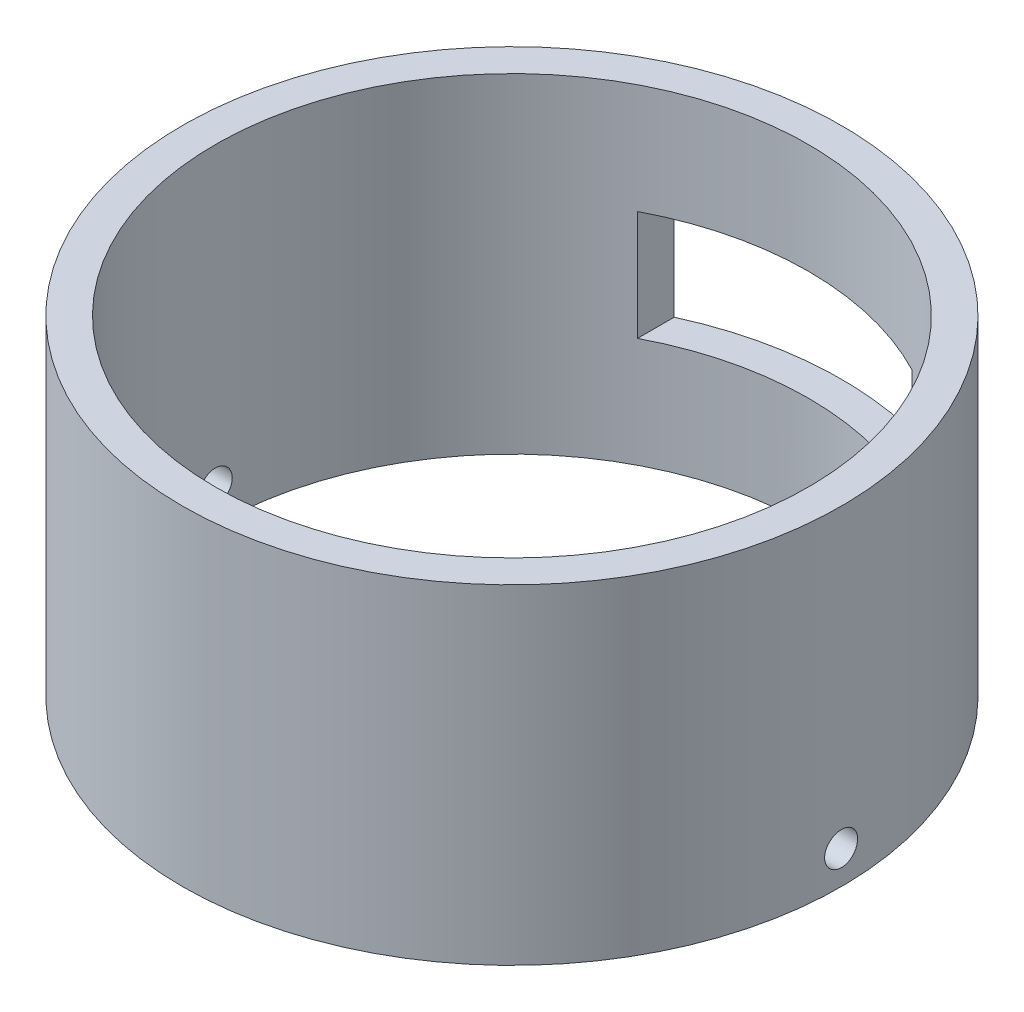
SolidWorks part; units mm, degrees
ref_plane "Front Plane" through (0, 0, 0) normal (0, 0, 1) x (1, 0, 0)
ref_plane "Top Plane" through (0, 0, 0) normal (0, 1, 0) x (1, 0, 0)
ref_plane "Right Plane" through (0, 0, 0) normal (1, 0, 0) x (0, 0, -1)
sketch "Sketch2" plane through (0, 0, 0) normal (0, 1, 0) x (1, 0, 0)
  circle A0 centre (0, 0) radius 30
  circle A1 centre (0, 0) radius 27
  dimension "D1" = 60
  dimension "D2" = 54
extrude "Boss-Extrude1" add sketch "Sketch2" along normal blind 30
sketch "Sketch3" plane through (0, 0, 0) normal (0, 0, 1) x (1, 0, 0)
  line L0 (-30, 0) -> (30, 0) construction
  line L1 (-12.5, 20) -> (12.5, 20)
  line L2 (-12.5, 20) -> (-12.5, 10)
  line L3 (-12.5, 10) -> (12.5, 10)
  line L4 (12.5, 20) -> (12.5, 10)
  line L5 (-12.5, 20) -> (12.5, 10) construction
  line L6 (-12.5, 10) -> (12.5, 20) construction
  line L7 (-30, 30) -> (-30, 0) construction
  point P0 (0, 15)
  dimension "D1" = 25
  dimension "D2" = 10
  dimension "D3" = 10
  dimension "D4" = 30
extrude "Cut-Extrude3" cut sketch "Sketch3" against normal blind 50
sketch "Sketch6" plane through (0, 0, 0) normal (1, 0, 0) x (0, 0, -1)
  line L0 (-30, 0) -> (30, 0) construction
  circle A0 centre (0, 3) radius 1.5
  dimension "D1" = 3
extrude "Cut-Extrude4" cut sketch "Sketch6" against normal through all both and the other way through all
